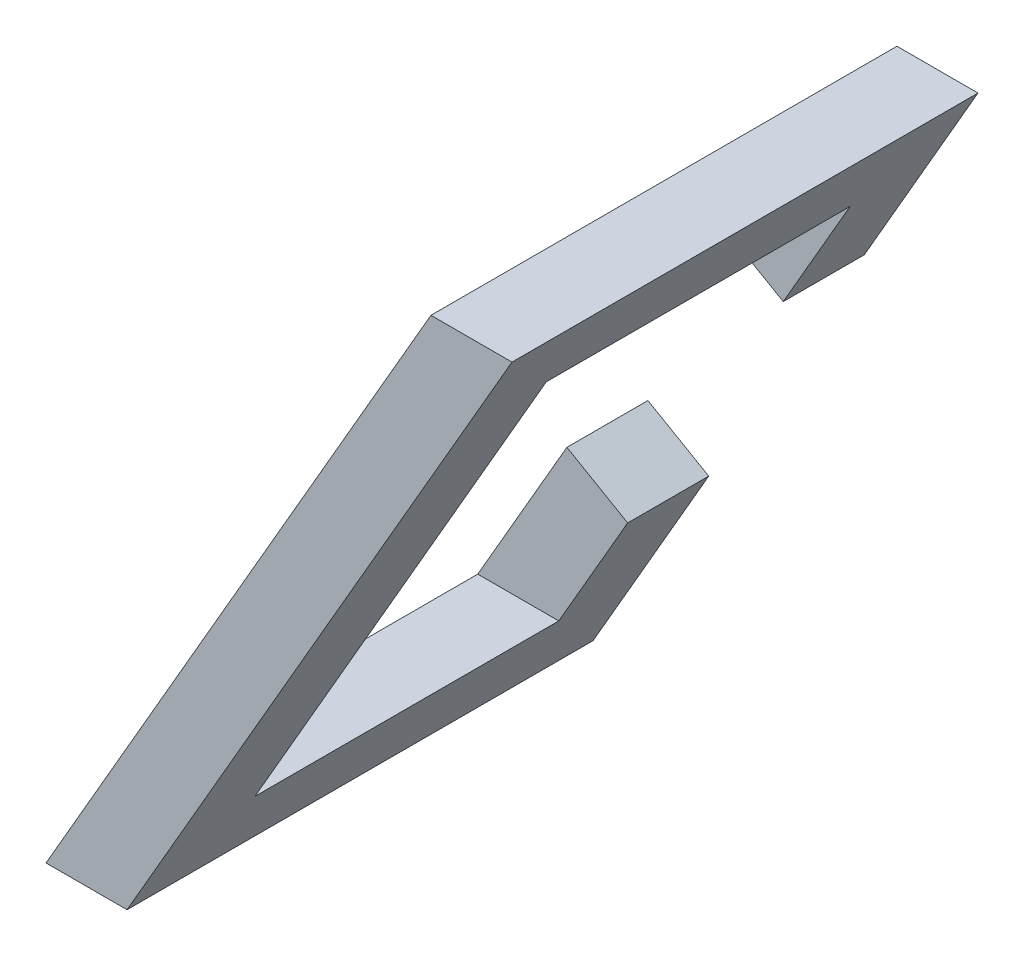
SolidWorks part; units mm, degrees
ref_plane "Front Plane" through (0, 0, 0) normal (0, 0, 1) x (1, 0, 0)
ref_plane "Top Plane" through (0, 0, 0) normal (0, 1, 0) x (1, 0, 0)
ref_plane "Right Plane" through (0, 0, 0) normal (1, 0, 0) x (0, 0, -1)
sketch "Sketch1" plane through (0, 0, 0) normal (0, 1, 0) x (1, 0, 0)
  circle A0 centre (0, 0) radius 3
  circle A1 centre (0, 0) radius 5
  dimension "D1" = 2
  dimension "D2" = 6
extrude "Boss-Extrude1" add sketch "Sketch1" along normal blind 7
sketch "Sketch2" plane through (0, 7, 0) normal (0, 1, 0) x (1, 0, 0)
  line L1 (4.5826, -2) -> (34.5826, -2)
  line L2 (34.5826, -2) -> (34.5826, 2)
  line L3 (34.5826, 2) -> (4.5826, 2)
  circle A1 centre (0, 0) radius 5 construction
  arc A2 (4.5826, 2) -> (4.5826, -2) centre (0, 0) ccw
  circle A3 centre (0, 0) radius 3
  dimension "D1" = 4
  dimension "D2" = 30
extrude "Boss-Extrude2" add sketch "Sketch2" against normal through all
sketch "Sketch3" plane through (0, 0, 2) normal (0, 0, 1) x (1, 0, 0)
  line L0 (4.5826, 0) -> (34.5826, 0) construction
  line L1 (13.7766, 0) -> (30.065, 0)
  line L2 (13.7766, 0) -> (13.7766, 13.1)
  line L3 (13.7766, 13.1) -> (30.065, 13.1)
  line L4 (30.065, 0) -> (30.065, 13.1)
extrude "Boss-Extrude3" add sketch "Sketch3" against normal blind 4
sketch "Sketch4" plane through (0, 0, 2) normal (0, 0, 1) x (1, 0, 0)
  line L0 (4.5826, 0) -> (34.5826, 0) construction
  line L1 (34.5826, 7) -> (30.065, 7)
  line L2 (34.5826, 7) -> (34.5826, 0)
  line L3 (34.5826, 0) -> (30.065, 0)
  line L4 (30.065, 7) -> (30.065, 0)
extrude "Cut-Extrude1" cut sketch "Sketch4" against normal blind 4
sketch "Sketch5" plane through (0, 0, 2) normal (0, 0, 1) x (1, 0, 0)
  line L12 (30.065, 13.1) -> (30.065, 0)
  line L13 (30.065, 0) -> (36.965, 0)
  line L14 (50.065, 13.1) -> (36.765, -0.2) construction
  line L15 (36.965, 0) -> (50.065, 13.1)
  line L16 (50.065, 13.1) -> (76.2256, 13.1)
  line L17 (89.565, 36.2045) -> (70.565, 3.2955) construction
  line L18 (76.2256, 13.1) -> (80.065, 19.75)
  line L19 (80.065, 19.75) -> (80.065, 26.4)
  line L20 (80.065, 26.4) -> (43.365, 26.4)
  line L21 (43.365, 26.4) -> (30.065, 13.1)
extrude "Boss-Extrude4" add sketch "Sketch5" against normal blind 4
sketch "Sketch6" plane through (0, 0, 2) normal (0, 0, 1) x (1, 0, 0)
  line L0 (64.2445, 36.2045) -> (68.2445, 36.2045)
  line L1 (64.2445, 36.2045) -> (45.2445, 3.2955)
  line L2 (68.2445, 36.2045) -> (49.2445, 3.2955)
  line L3 (45.2445, 3.2955) -> (49.2445, 3.2955)
  line L4 (85.565, 36.2045) -> (89.565, 36.2045)
  line L5 (85.565, 36.2045) -> (66.565, 3.2955)
  line L6 (89.565, 36.2045) -> (70.565, 3.2955)
  line L7 (66.565, 3.2955) -> (70.565, 3.2955)
extrude "Boss-Extrude5" add sketch "Sketch6" against normal blind 4
sketch "Sketch7" plane through (0, 0, 2) normal (0, 0, 1) x (1, 0, 0)
  line L0 (68.2445, 36.2045) -> (64.2445, 36.2045)
  line L1 (68.2445, 36.2045) -> (65.9351, 32.2045)
  line L2 (64.2445, 36.2045) -> (61.9351, 32.2045)
  line L3 (65.9351, 32.2045) -> (61.9351, 32.2045)
  line L4 (64.2445, 36.2045) -> (58.5838, 26.4) construction
  line L5 (85.565, 36.2045) -> (89.565, 36.2045)
  line L6 (85.565, 36.2045) -> (83.2556, 32.2045)
  line L7 (89.565, 36.2045) -> (87.2556, 32.2045)
  line L8 (83.2556, 32.2045) -> (87.2556, 32.2045)
  line L9 (70.565, 3.2955) -> (89.565, 36.2045) construction
  line L10 (66.565, 3.2955) -> (70.565, 3.2955)
  line L11 (66.565, 3.2955) -> (68.8744, 7.2955)
  line L12 (70.565, 3.2955) -> (72.8744, 7.2955)
  line L13 (68.8744, 7.2955) -> (72.8744, 7.2955)
  line L14 (70.565, 3.2955) -> (89.565, 36.2045) construction
  line L15 (45.2445, 3.2955) -> (49.2445, 3.2955)
  line L16 (45.2445, 3.2955) -> (47.5539, 7.2955)
  line L17 (49.2445, 3.2955) -> (51.5539, 7.2955)
  line L18 (47.5539, 7.2955) -> (51.5539, 7.2955)
  line L19 (49.2445, 3.2955) -> (54.9051, 13.1) construction
  dimension "D1" = 4
extrude "Boss-Extrude6" add sketch "Sketch7" along normal blind 19
sketch "Sketch8" plane through (0, 0, 21) normal (0, 0, 1) x (1, 0, 0)
  line L0 (64.2445, 36.2045) -> (68.2445, 36.2045)
  line L1 (64.2445, 36.2045) -> (45.2445, 3.2955)
  line L2 (68.2445, 36.2045) -> (49.2445, 3.2955)
  line L3 (45.2445, 3.2955) -> (49.2445, 3.2955)
  line L4 (85.565, 36.2045) -> (89.565, 36.2045)
  line L5 (85.565, 36.2045) -> (66.565, 3.2955)
  line L6 (89.565, 36.2045) -> (70.565, 3.2955)
  line L7 (66.565, 3.2955) -> (70.565, 3.2955)
extrude "Boss-Extrude7" add sketch "Sketch8" against normal blind 4
sketch "Sketch9" plane through (0, 0, -2) normal (0, 0, -1) x (-1, 0, 0)
  line L0 (-54.9051, 13.1) -> (-62.5838, 26.4)
  line L1 (-54.9051, 13.1) -> (-76.274, 13.1838)
  line L2 (-62.5838, 26.4) -> (-83.9527, 26.4838)
  line L3 (-76.274, 13.1838) -> (-83.9527, 26.4838)
  line L4 (-70.565, 3.2955) -> (-89.565, 36.2045) construction
extrude "Boss-Extrude8" add sketch "Sketch9" along normal blind 8.1
sketch "Sketch10" plane through (51.4967, -29.7316, 0) normal (0.866, -0.5, 0) x (0, 0, -1)
  line L0 (-2, 42.7553) -> (-2, 71.5177) construction
  line L1 (10.1, 64.912) -> (-2, 64.912)
  line L2 (10.1, 64.912) -> (10.1, 49.5545)
  line L3 (10.1, 49.5545) -> (-2, 49.5545)
  line L4 (-2, 64.912) -> (-2, 49.5545)
  line L5 (10.1, 49.5545) -> (2, 49.5545) construction
  dimension "D1" = 0
extrude "Cut-Extrude2" cut sketch "Sketch10" against normal through all
sketch "Sketch11" plane through (48.4967, -27.9996, 0) normal (-0.866, 0.5, 0) x (0, 0, 1)
  line L1 (-20.1346, 86.7368) -> (39.2852, 86.7368)
  line L2 (-20.1346, 86.7368) -> (-20.1346, 23.8139)
  line L4 (39.2852, 86.7368) -> (39.2852, 23.8139)
  line L6 (-20.1346, 23.8139) -> (-20.1346, -9.6318)
  line L7 (-20.1346, -9.6318) -> (39.2852, -9.6318)
  line L8 (39.2852, 23.8139) -> (39.2852, -9.6318)
extrude "Cut-Extrude3" cut sketch "Sketch11" along normal through all
sketch "Sketch12" plane through (51.4967, -29.7316, 0) normal (0.866, -0.5, 0) x (0, 0, -1)
  line L1 (2, 49.5545) -> (12.3118, 49.5545)
  line L2 (2, 49.5545) -> (2, 44.6938)
  line L3 (2, 44.6938) -> (12.3118, 44.6938)
  line L4 (12.3118, 49.5545) -> (12.3118, 44.6938)
extrude "Cut-Extrude4" cut sketch "Sketch12" against normal blind 10
